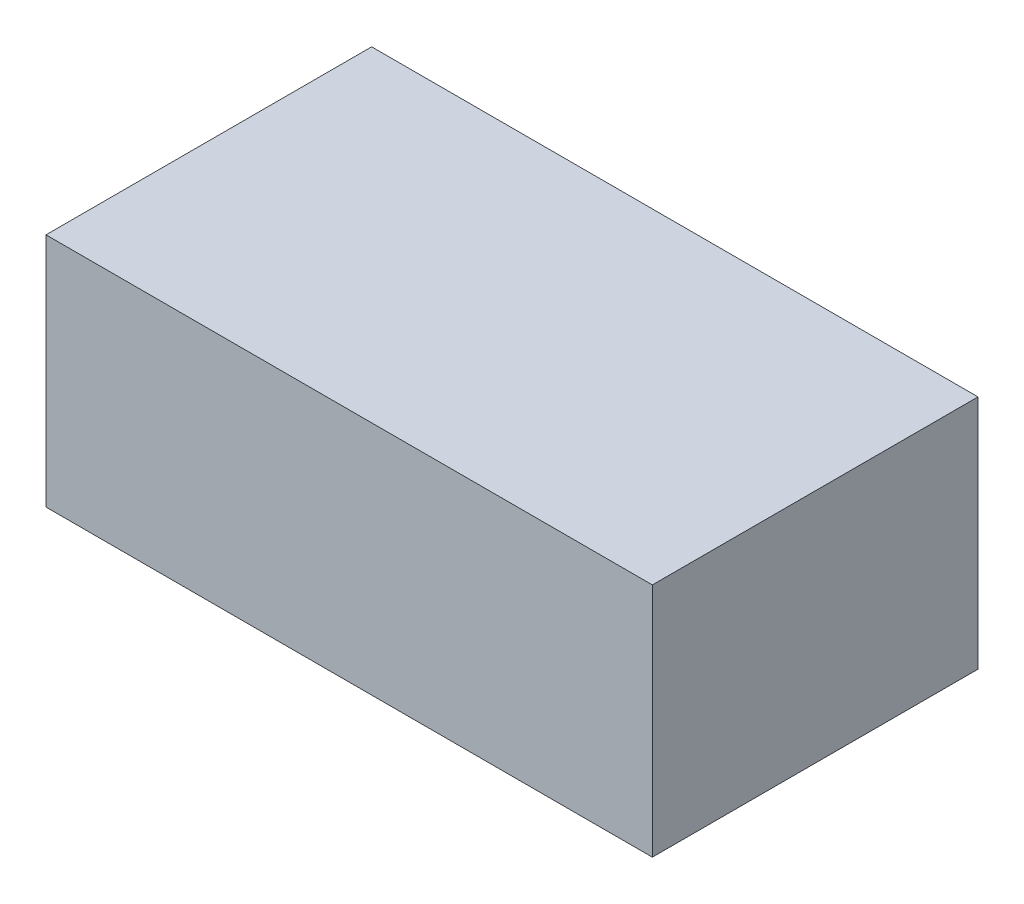
SolidWorks part; units mm, degrees
ref_plane "Front Plane" through (0, 0, 0) normal (0, 0, 1) x (1, 0, 0)
ref_plane "Top Plane" through (0, 0, 0) normal (0, 1, 0) x (1, 0, 0)
ref_plane "Right Plane" through (0, 0, 0) normal (1, 0, 0) x (0, 0, -1)
sketch "Sketch1" plane through (0, 0, 0) normal (0, 1, 0) x (1, 0, 0)
  line L1 (0, 0) -> (54, 0)
  line L2 (0, 0) -> (0, 29)
  line L3 (0, 29) -> (54, 29)
  line L4 (54, 0) -> (54, 29)
  dimension "D1" = 54
  dimension "D2" = 29
extrude "Boss-Extrude1" add sketch "Sketch1" along normal blind 21
